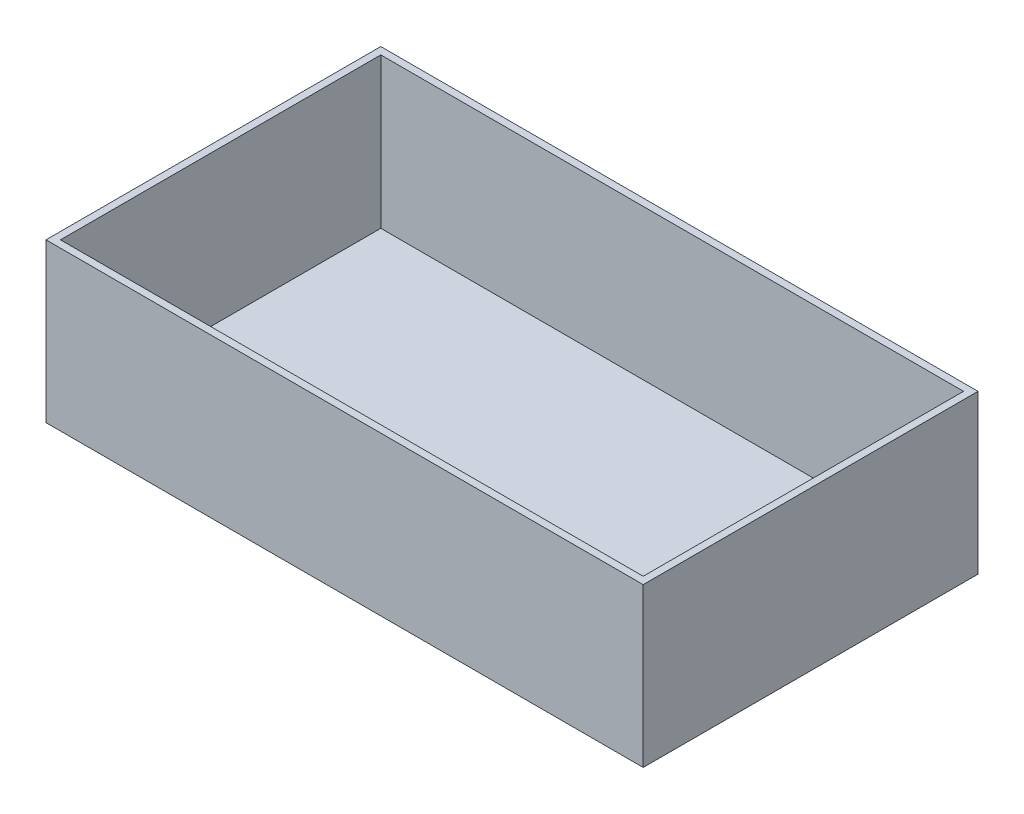
SolidWorks part; units mm, degrees
ref_plane "Alzado" through (0, 0, 0) normal (0, 0, 1) x (1, 0, 0)
ref_plane "Planta" through (0, 0, 0) normal (0, 1, 0) x (1, 0, 0)
ref_plane "Vista lateral" through (0, 0, 0) normal (1, 0, 0) x (0, 0, -1)
sketch "Croquis1" plane through (0, 0, 0) normal (0, 1, 0) x (1, 0, 0)
  line L1 (-660, -370) -> (660, -370)
  line L2 (-660, -370) -> (-660, 370)
  line L3 (-660, 370) -> (660, 370)
  line L4 (660, -370) -> (660, 370)
  line L5 (-660, -370) -> (660, 370) construction
  line L6 (-660, 370) -> (660, -370) construction
  point P0 (0, 0)
  dimension "D1" = 740
  dimension "D2" = 1320
extrude "Saliente-Extruir1" add sketch "Croquis1" along normal blind 350
sketch "Croquis2" plane through (0, 350, 0) normal (0, 1, 0) x (1, 0, 0)
  line L1 (-644, -354) -> (644, -354)
  line L2 (-644, -354) -> (-644, 354)
  line L3 (-644, 354) -> (644, 354)
  line L4 (644, -354) -> (644, 354)
  line L5 (-644, -354) -> (644, 354) construction
  line L6 (-644, 354) -> (644, -354) construction
  line L7 (-660, 370) -> (-660, -370) construction
  line L8 (660, 370) -> (-660, 370) construction
  point P0 (0, 0)
  dimension "D1" = 16
  dimension "D2" = 16
extrude "Cortar-Extruir1" cut sketch "Croquis2" against normal blind 332
